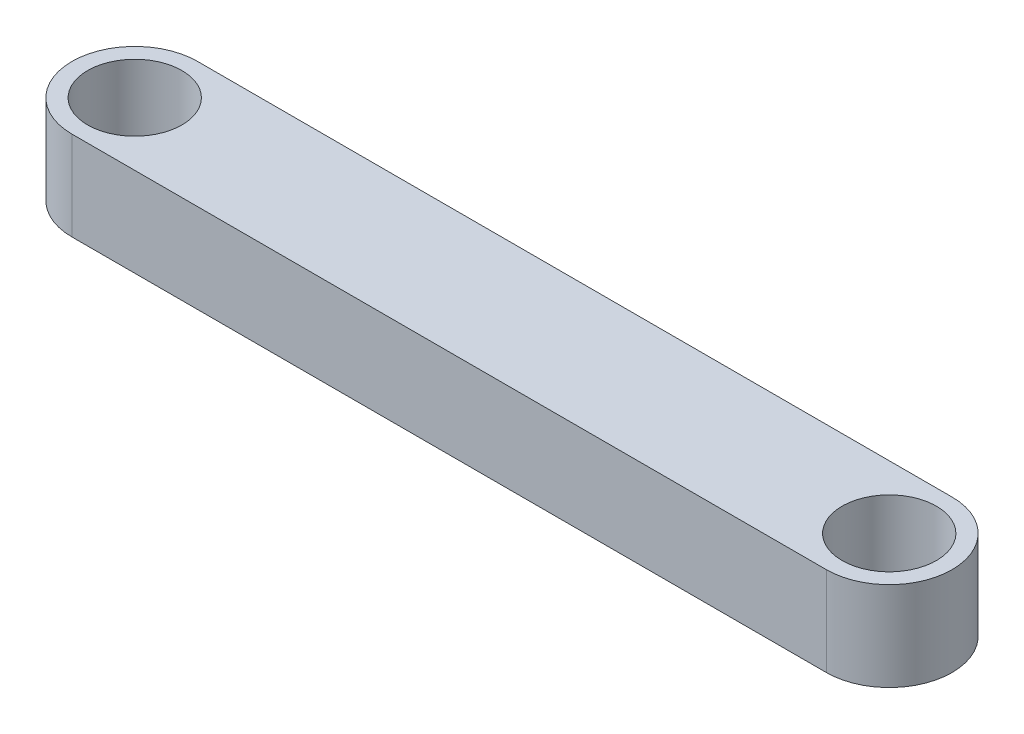
SolidWorks part; units mm, degrees
ref_plane "Front Plane" through (0, 0, 0) normal (0, 0, 1) x (1, 0, 0)
ref_plane "Top Plane" through (0, 0, 0) normal (0, 1, 0) x (1, 0, 0)
ref_plane "Right Plane" through (0, 0, 0) normal (1, 0, 0) x (0, 0, -1)
sketch "Sketch1" plane through (0, 0, 0) normal (0, 1, 0) x (1, 0, 0)
  line L1 (-158.75, -26.4583) -> (158.75, -26.4583)
  line L3 (-158.75, 26.4583) -> (158.75, 26.4583)
  line L5 (-158.75, -26.4583) -> (158.75, 26.4583) construction
  line L6 (-158.75, 26.4583) -> (158.75, -26.4583) construction
  arc A0 (158.75, 26.4583) -> (158.75, -26.4583) centre (158.75, 0) cw
  arc A1 (-158.75, 26.4583) -> (-158.75, -26.4583) centre (-158.75, 0) ccw
  circle A2 centre (-158.75, 0) radius 19.8438
  circle A3 centre (158.75, 0) radius 19.8438
  point P0 (0, 0)
  dimension "Knuckle Diameter" = 39.6875
  dimension "Link Length" = 317.5
  dimension "Link Width" = 52.9167
extrude "Boss-Extrude1" add sketch "Sketch1" along normal blind 37.5 contours L3 A0 L1 A1
